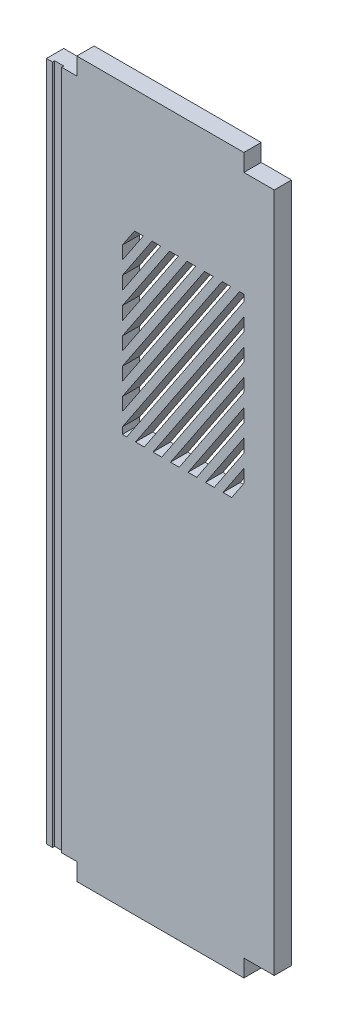
SolidWorks part; units mm, degrees
ref_plane "Front Plane" through (0, 0, 0) normal (0, 0, 1) x (1, 0, 0)
ref_plane "Top Plane" through (0, 0, 0) normal (0, 1, 0) x (1, 0, 0)
ref_plane "Right Plane" through (0, 0, 0) normal (1, 0, 0) x (0, 0, -1)
sketch "Sketch1" plane through (0, 0, 0) normal (0, 0, 1) x (1, 0, 0)
  line L1 (0, 0) -> (75, 0)
  line L2 (0, 0) -> (0, 235.4)
  line L3 (0, 235.4) -> (75, 235.4)
  line L4 (75, 0) -> (75, 235.4)
  dimension "D1" = 235.4
  dimension "D2" = 75
extrude "Boss-Extrude1" add sketch "Sketch1" along normal blind 5.7
sketch "Sketch2" plane through (0, 0, 0) normal (0, 0, -1) x (-1, 0, 0)
  line L2 (-75, 0) -> (-65, 0)
  line L3 (-75, 0) -> (-75, 5.7)
  line L4 (-75, 5.7) -> (-65, 5.7)
  line L6 (-65, 0) -> (-65, 5.7)
  line L7 (0, 0) -> (-10, 0)
  line L8 (0, 0) -> (0, 5.7)
  line L9 (0, 5.7) -> (-10, 5.7)
  line L12 (-10, 0) -> (-10, 5.7)
  line L13 (0, 235.4) -> (-10, 235.4)
  line L14 (0, 235.4) -> (0, 229.7)
  line L15 (0, 229.7) -> (-10, 229.7)
  line L16 (-10, 235.4) -> (-10, 229.7)
  line L17 (-75, 235.4) -> (-65, 235.4)
  line L18 (-75, 235.4) -> (-75, 229.7)
  line L19 (-75, 229.7) -> (-65, 229.7)
  line L20 (-65, 235.4) -> (-65, 229.7)
  dimension "D1" = 5.7
  dimension "D2" = 5.7
  dimension "D3" = 10
  dimension "D4" = 10
  dimension "D5" = 10
  dimension "D6" = 5.7
  dimension "D7" = 5.7
  dimension "D8" = 10
extrude "Cut-Extrude1" cut sketch "Sketch2" against normal blind 5.7
sketch "Sketch3" plane through (0, 0, 5.7) normal (0, 0, 1) x (1, 0, 0)
  line L1 (75, 5.7) -> (75, 229.7) construction
  line L39 (65, 195) -> (25, 135) construction
  line L40 (25, 195) -> (65, 195)
  line L41 (25, 195) -> (25, 135)
  line L42 (25, 135) -> (65, 135)
  line L43 (65, 195) -> (65, 135)
  line L44 (63.5578, 195) -> (25, 137.1633)
  line L45 (65, 192.8367) -> (26.4422, 135)
  line L46 (45, 165) -> (25, 165) construction
  line L47 (45, 165) -> (65, 165) construction
  line L48 (60.6778, 195) -> (25, 141.4833)
  line L49 (57.7978, 195) -> (25, 145.8033)
  line L50 (54.9178, 195) -> (25, 150.1233)
  line L51 (52.0378, 195) -> (25, 154.4433)
  line L52 (49.1578, 195) -> (25, 158.7633)
  line L53 (46.2778, 195) -> (25, 163.0833)
  line L54 (43.3978, 195) -> (25, 167.4033)
  line L55 (40.5178, 195) -> (25, 171.7233)
  line L56 (37.6378, 195) -> (25, 176.0433)
  line L57 (34.7578, 195) -> (25, 180.3633)
  line L58 (31.8778, 195) -> (25, 184.6833)
  line L59 (28.9978, 195) -> (25, 189.0033)
  line L60 (26.1178, 195) -> (25, 193.3233)
  line L61 (65, 188.5167) -> (29.3222, 135)
  line L62 (65, 184.1967) -> (32.2022, 135)
  line L63 (65, 179.8767) -> (35.0822, 135)
  line L64 (65, 175.5567) -> (37.9622, 135)
  line L65 (65, 171.2367) -> (40.8422, 135)
  line L66 (65, 166.9167) -> (43.7222, 135)
  line L67 (65, 162.5967) -> (46.6022, 135)
  line L68 (65, 158.2767) -> (49.4822, 135)
  line L69 (65, 153.9567) -> (52.3622, 135)
  line L70 (65, 149.6367) -> (55.2422, 135)
  line L71 (65, 145.3167) -> (58.1222, 135)
  line L72 (65, 140.9967) -> (61.0022, 135)
  line L73 (65, 136.6767) -> (63.8822, 135)
  line L74 (10, 0) -> (65, 0) construction
  point P79 (43.5578, 165)
  point P82 (46.4422, 165)
  dimension "D7" = 40
  dimension "D8" = 165
  dimension "D9" = 30
  dimension "D10" = 1.2
  dimension "D11" = 2.3963
  dimension "D12" = 2.3963
  dimension "D13" = 2.3963
  dimension "D14" = 2.3963
  dimension "D15" = 2.3963
  dimension "D16" = 2.3963
  dimension "D17" = 2.3963
  dimension "D18" = 2.3963
  dimension "D19" = 2.3963
  dimension "D20" = 2.3963
  dimension "D21" = 2.3963
  dimension "D22" = 2.3963
  dimension "D23" = 2.3963
  dimension "D24" = 2.3963
  dimension "D25" = 2.3963
  dimension "D26" = 2.3963
  dimension "D27" = 2.3963
  dimension "D28" = 2.3963
  dimension "D29" = 2.3963
  dimension "D30" = 2.3963
  dimension "D31" = 2.3963
  dimension "D32" = 2.3963
  dimension "D33" = 2.3963
  dimension "D34" = 2.3963
  dimension "D35" = 2.3963
  dimension "D36" = 2.3963
  dimension "D37" = 60
extrude "Cut-Extrude2" cut sketch "Sketch3" against normal blind 5.7 contours L45 L43 L40 L44 L41 L42 | L40 L49 L41 L48 | L40 L51 L41 L50 | L40 L53 L41 L52 | L40 L55 L41 L54 | L40 L57 L41 L56 | L40 L59 L41 L58 | L62 L43 L61 L42 | L64 L43 L63 L42 | L66 L43 L65 L42 | L68 L43 L67 L42 | L70 L43 L69 L42 | L72 L43 L71 L42
sketch "Sketch4" plane through (0, 0, 5.7) normal (0, 0, 1) x (1, 0, 0)
  line L0 (10, 229.7) -> (0, 229.7) construction
  line L1 (2, 229.7) -> (5, 229.7)
  line L2 (2, 229.7) -> (2, 5.7)
  line L3 (2, 5.7) -> (5, 5.7)
  line L4 (5, 229.7) -> (5, 5.7)
  line L5 (0, 5.7) -> (10, 5.7) construction
  line L6 (0, 229.7) -> (0, 5.7) construction
  dimension "D1" = 2
  dimension "D2" = 3
extrude "Cut-Extrude3" cut sketch "Sketch4" against normal blind 0.7
